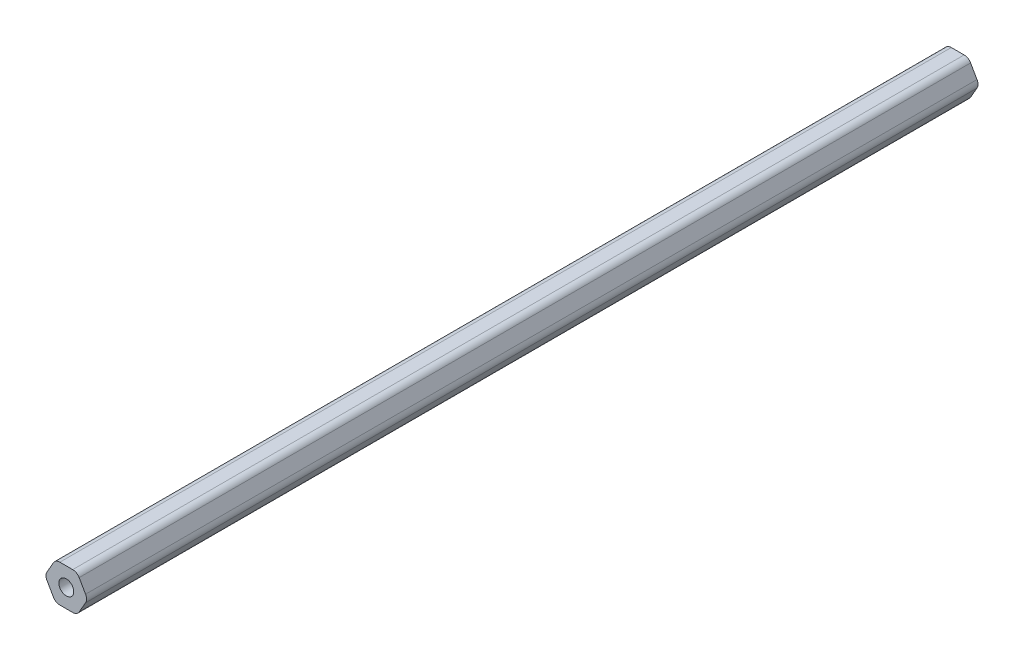
SolidWorks part; units mm, degrees
ref_plane "Front Plane" through (0, 0, 0) normal (0, 0, 1) x (1, 0, 0)
ref_plane "Top Plane" through (0, 0, 0) normal (0, 1, 0) x (1, 0, 0)
ref_plane "Right Plane" through (0, 0, 0) normal (1, 0, 0) x (0, 0, -1)
sketch "Sketch1" plane through (0, 0, 0) normal (0, 0, 1) x (1, 0, 0)
  line L1 (0.9823, -1.3778) -> (-2.6838, 4.9722)
  line L2 (-2.6838, 4.9722) -> (-10.0162, 4.9722)
  line L3 (-10.0162, 4.9722) -> (-13.6823, -1.3778)
  line L4 (-13.6823, -1.3778) -> (-10.0162, -7.7278)
  line L5 (-10.0162, -7.7278) -> (-2.6838, -7.7278)
  line L6 (-2.6838, -7.7278) -> (0.9823, -1.3778)
  circle A0 centre (-6.35, -1.3778) radius 6.35 construction
  circle A1 centre (-6.35, -1.3778) radius 2.54
  dimension "D1" = 12.7
extrude "Boss-Extrude1" add sketch "Sketch1" along normal blind 304.8
fillet "Fillet1" radius 2.54 6 edges at (-2.6838, -7.7278, 152.4) (-10.0162, -7.7278, 152.4) (-13.6823, -1.3778, 152.4) (-10.0162, 4.9722, 152.4) (-2.6838, 4.9722, 152.4) (0.9823, -1.3778, 152.4)
